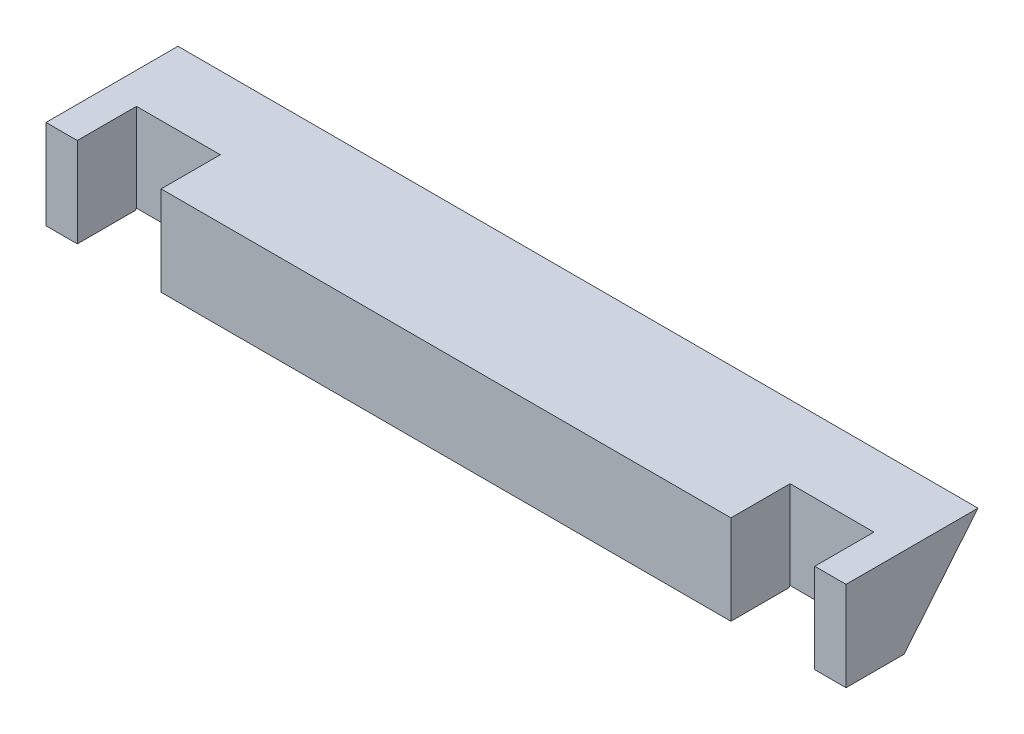
SolidWorks part; units mm, degrees
ref_plane "前视基准面" through (0, 0, 0) normal (0, 0, 1) x (1, 0, 0)
ref_plane "上视基准面" through (0, 0, 0) normal (0, 1, 0) x (1, 0, 0)
ref_plane "右视基准面" through (0, 0, 0) normal (1, 0, 0) x (0, 0, -1)
sketch "草图1" plane through (0, 0, 0) normal (1, 0, 0) x (0, 0, -1)
  line L0 (51.7112, 31.8223) -> (-12.5088, 31.8223)
  line L1 (-12.5088, 31.8223) -> (-12.5088, -45.9877)
  line L2 (-12.5088, -45.9877) -> (51.7112, 31.8223)
extrude "凸台-拉伸1" add sketch "草图1" along normal blind 695
sketch "草图2" plane through (0, 0, 12.5088) normal (0, 0, 1) x (1, 0, 0)
  line L1 (0, 31.8223) -> (695, 31.8223)
  line L2 (0, 31.8223) -> (0, -45.9877)
  line L3 (0, -45.9877) -> (695, -45.9877)
  line L4 (695, 31.8223) -> (695, -45.9877)
extrude "凸台-拉伸2" add sketch "草图2" along normal blind 50.41
sketch "草图3" plane through (0, 31.8223, 0) normal (0, 1, 0) x (1, 0, 0)
  line L0 (0, 51.7112) -> (0, -62.9188) construction
  line L1 (0, -5.6038) -> (27.19, -5.6038)
  line L2 (0, -5.6038) -> (0, -62.9188)
  line L3 (0, -62.9188) -> (27.19, -62.9188)
  line L4 (27.19, -5.6038) -> (27.19, -62.9188)
  line L5 (695, -62.9188) -> (0, -62.9188) construction
sketch "草图4" plane through (0, 31.8223, 0) normal (0, 1, 0) x (1, 0, 0)
  line L1 (695, -62.9188) -> (667.81, -62.9188)
  line L2 (695, -62.9188) -> (695, -11.5188)
  line L3 (695, -11.5188) -> (667.81, -11.5188)
  line L4 (667.81, -62.9188) -> (667.81, -11.5188)
  line L5 (27.19, -62.9188) -> (100.01, -62.9188)
  line L6 (27.19, -62.9188) -> (27.19, -11.5188)
  line L7 (27.19, -11.5188) -> (100.01, -11.5188)
  line L8 (100.01, -62.9188) -> (100.01, -11.5188)
  dimension "D1" = 72.82
  dimension "D2" = 51.4
  dimension "D3" = 27.19
sketch "草图9" plane through (0, 31.8223, 0) normal (0, 1, 0) x (1, 0, 0)
  line L0 (27.19, -11.5188) -> (100.01, -11.5188) construction
  line L3 (27.19, -62.9188) -> (100.01, -62.9188) construction
  line L6 (100.01, -62.9188) -> (27.19, -62.9188)
  line L7 (100.01, -62.9188) -> (100.01, -11.5188)
  line L8 (100.01, -11.5188) -> (27.19, -11.5188)
  line L9 (27.19, -62.9188) -> (27.19, -11.5188)
extrude "切除-拉伸3" cut sketch "草图9" against normal blind 1000
sketch "草图10" plane through (0, 31.8223, 0) normal (0, 1, 0) x (1, 0, 0)
  line L1 (667.81, -62.9188) -> (594.99, -62.9188)
  line L2 (667.81, -62.9188) -> (667.81, -11.5188)
  line L3 (667.81, -11.5188) -> (594.99, -11.5188)
  line L4 (594.99, -62.9188) -> (594.99, -11.5188)
extrude "切除-拉伸4" cut sketch "草图10" against normal blind 1000
